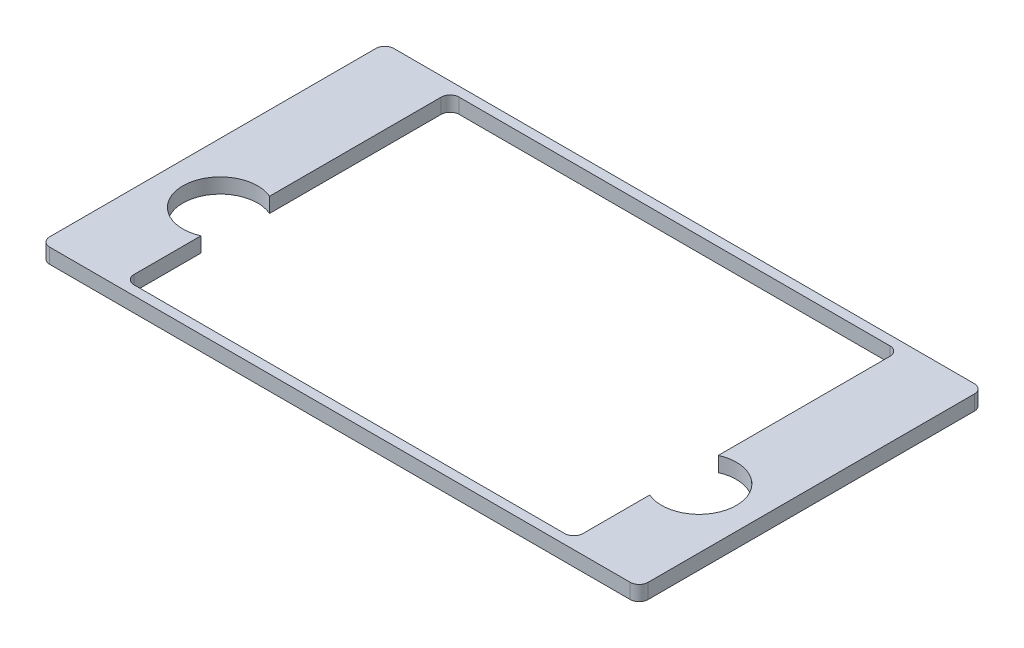
SolidWorks part; units mm, degrees
ref_plane "Front Plane" through (0, 0, 0) normal (0, 0, 1) x (1, 0, 0)
ref_plane "Top Plane" through (0, 0, 0) normal (0, 1, 0) x (1, 0, 0)
ref_plane "Right Plane" through (0, 0, 0) normal (1, 0, 0) x (0, 0, -1)
sketch "Sketch1" plane through (0, 0, 0) normal (0, 1, 0) x (1, 0, 0)
  line L1 (3.81, 0) -> (250.19, 0)
  line L2 (0, 3.81) -> (0, 142.24)
  line L3 (3.81, 146.05) -> (250.19, 146.05)
  line L4 (254, 3.81) -> (254, 142.24)
  line L5 (35.56, 142.025) -> (218.44, 142.025)
  line L6 (31.75, 138.215) -> (31.75, 7.835)
  line L7 (35.56, 4.025) -> (218.44, 4.025)
  line L8 (222.25, 138.215) -> (222.25, 7.835)
  arc A0 (250.19, 0) -> (254, 3.81) centre (250.19, 3.81) ccw
  arc A1 (250.19, 146.05) -> (254, 142.24) centre (250.19, 142.24) cw
  arc A2 (0, 142.24) -> (3.81, 146.05) centre (3.81, 142.24) cw
  arc A3 (3.81, 0) -> (0, 3.81) centre (3.81, 3.81) cw
  arc A4 (31.75, 7.835) -> (35.56, 4.025) centre (35.56, 7.835) ccw
  arc A5 (218.44, 4.025) -> (222.25, 7.835) centre (218.44, 7.835) ccw
  arc A6 (218.44, 142.025) -> (222.25, 138.215) centre (218.44, 138.215) cw
  arc A7 (35.56, 142.025) -> (31.75, 138.215) centre (35.56, 138.215) ccw
  point P11 (254, 0)
  point P14 (254, 146.05)
  point P17 (0, 146.05)
  point P20 (0, 0)
  point P25 (222.25, 4.025)
  point P28 (222.25, 142.025)
  point P31 (31.75, 142.025)
  dimension "D7" = 3.81
  dimension "D1" = 254
  dimension "D2" = 146.05
  dimension "D3" = 138
  dimension "D4" = 190.5
  dimension "D5" = 4.025
  dimension "D6" = 31.75
extrude "Boss-Extrude1" add sketch "Sketch1" along normal blind 6.35
sketch "Sketch2" plane through (0, 6.35, 0) normal (0, 1, 0) x (1, 0, 0)
  line L0 (3.81, 0) -> (250.19, 0) construction
  line L1 (0, 142.24) -> (0, 3.81) construction
  line L2 (254, 3.81) -> (254, 142.24) construction
  circle A0 centre (25.4, 50.8) radius 15.875
  circle A1 centre (228.6, 50.8) radius 15.875
  dimension "D3" = 31.75
  dimension "D4" = 31.75
  dimension "D1" = 50.8
  dimension "D2" = 50.8
  dimension "D5" = 25.4
  dimension "D6" = 25.4
extrude "Cut-Extrude1" cut sketch "Sketch2" against normal through all
equation "\"D5@Sketch1\"=(\"D2@Sketch1\"-\"D3@Sketch1\")/2"
equation "\"D6@Sketch1\"=(\"D1@Sketch1\"-\"D4@Sketch1\")/2"
